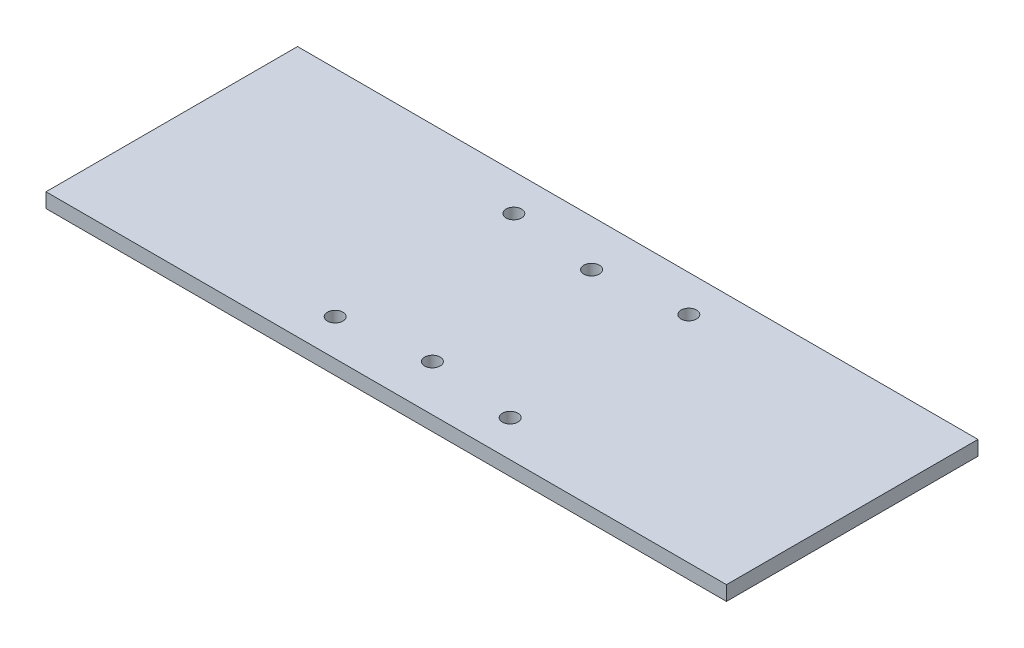
SolidWorks part; units mm, degrees
ref_plane "前视基准面" through (0, 0, 0) normal (0, 0, 1) x (1, 0, 0)
ref_plane "上视基准面" through (0, 0, 0) normal (0, 1, 0) x (1, 0, 0)
ref_plane "右视基准面" through (0, 0, 0) normal (1, 0, 0) x (0, 0, -1)
other "Configuration Table"
sketch "草图1" plane through (0, 0, 0) normal (0, 1, 0) x (1, 0, 0)
  line L1 (-41.9496, 51.75) -> (98.0504, 51.75)
  line L2 (-41.9496, 51.75) -> (-41.9496, 0)
  line L3 (-41.9496, 0) -> (98.0504, 0)
  line L4 (98.0504, 51.75) -> (98.0504, 0)
  dimension "D1" = 51.75
  dimension "D2" = 140
extrude "凸台-拉伸1" add sketch "草图1" along normal blind 3
sketch "草图2" plane through (0, 3, 0) normal (0, 1, 0) x (1, 0, 0)
  line L0 (-41.9496, 0) -> (98.0504, 0) construction
  circle A0 centre (28.0504, 9.5) radius 1.6
  circle A1 centre (46.0504, 7.5) radius 1.6
  circle A2 centre (10.0504, 7.5) radius 1.6
  point P3 (28.0504, 0)
  dimension "D1" = 9.5
  dimension "D2" = 70
  dimension "D3" = 18
  dimension "D4" = 2
  dimension "D5" = 18
  dimension "D6" = 7.5
  dimension "D7" = 2
extrude "切除-拉伸1" cut sketch "草图2" against normal through all both and the other way through all
sketch "草图3" plane through (0, 3, 0) normal (0, 1, 0) x (1, 0, 0)
  line L0 (98.0504, 51.75) -> (-41.9496, 51.75) construction
  circle A0 centre (10.0504, 44.25) radius 1.6
  circle A1 centre (28.0504, 42.25) radius 1.6
  circle A2 centre (46.0504, 44.25) radius 1.6
  point P0 (22.0825, 52.1483)
  dimension "D1" = 18
  dimension "D2" = 36
  dimension "D3" = 2
  dimension "D4" = 2
  dimension "D5" = 9.5
extrude "切除-拉伸2" cut sketch "草图3" against normal blind 10
